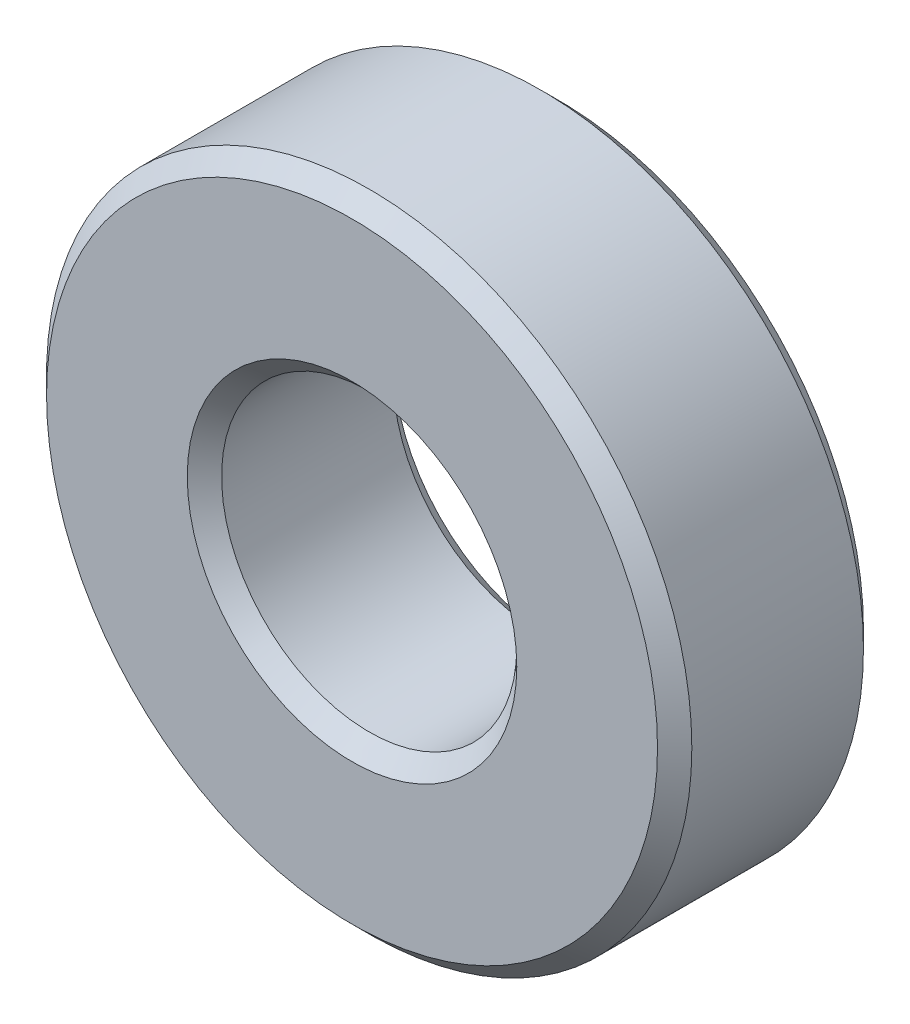
SolidWorks part; units mm, degrees
ref_plane "Front Plane" through (0, 0, 0) normal (0, 0, 1) x (1, 0, 0)
ref_plane "Top Plane" through (0, 0, 0) normal (0, 1, 0) x (1, 0, 0)
ref_plane "Right Plane" through (0, 0, 0) normal (1, 0, 0) x (0, 0, -1)
sketch "Sketch1" plane through (0, 0, 0) normal (0, 0, 1) x (1, 0, 0)
  circle A0 centre (0, 0) radius 9.4
  circle A1 centre (0, 0) radius 4.3
  dimension "D1" = 18.8
  dimension "D2" = 8.6
extrude "Boss-Extrude1" add sketch "Sketch1" along normal blind 6
chamfer "Chamfer1" distance 0.5 angle 45 4 edges at (4.3, 0, 0) (9.4, 0, 0) (4.3, 0, 6) (9.4, 0, 6)
